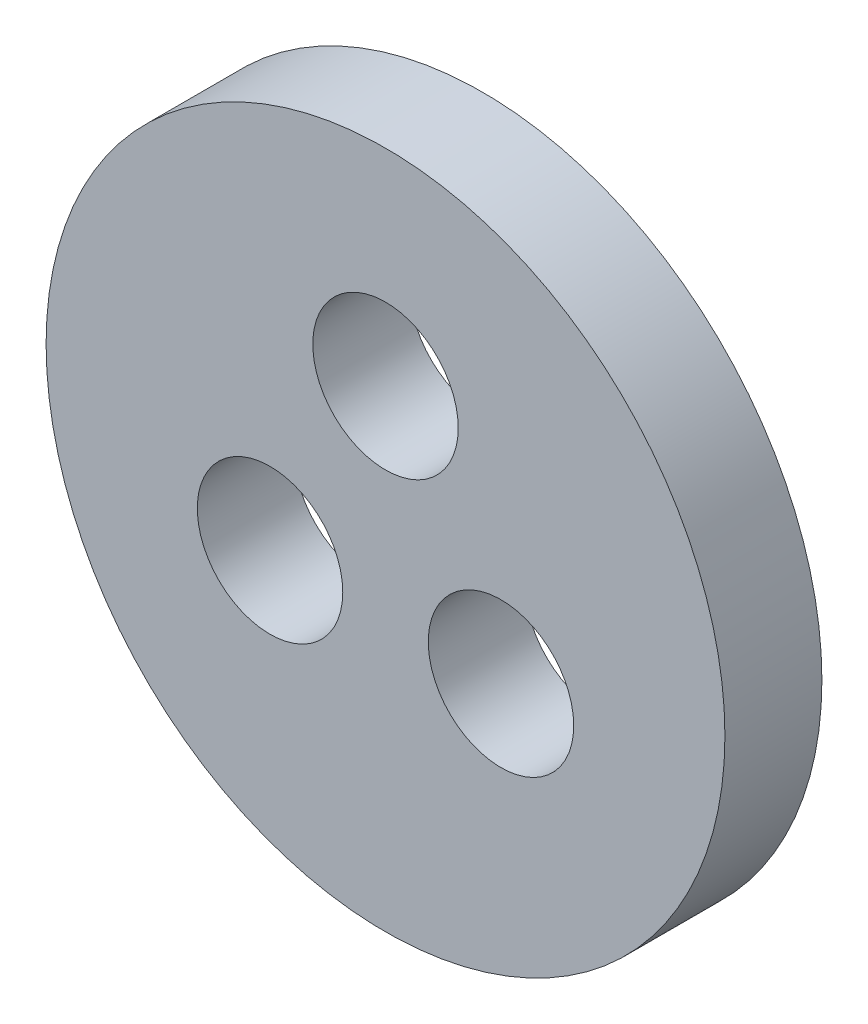
SolidWorks part; units mm, degrees
ref_plane "Front Plane" through (0, 0, 0) normal (0, 0, 1) x (1, 0, 0)
ref_plane "Top Plane" through (0, 0, 0) normal (0, 1, 0) x (1, 0, 0)
ref_plane "Right Plane" through (0, 0, 0) normal (1, 0, 0) x (0, 0, -1)
sketch "Sketch1" plane through (0, 0, 0) normal (0, 0, 1) x (1, 0, 0)
  circle A0 centre (0, 0) radius 11.1125
  circle A1 centre (0, 4.3656) radius 2.3813
  circle A2 centre (3.7807, -2.1828) radius 2.3813
  circle A3 centre (-3.7807, -2.1828) radius 2.3813
  point P11 (0, 0)
  dimension "D1" = 22.225
  dimension "D2" = 4.7625
  dimension "D3" = 4.3656
  dimension "D4" = 3
extrude "Boss-Extrude1" add sketch "Sketch1" along normal blind 3.175
